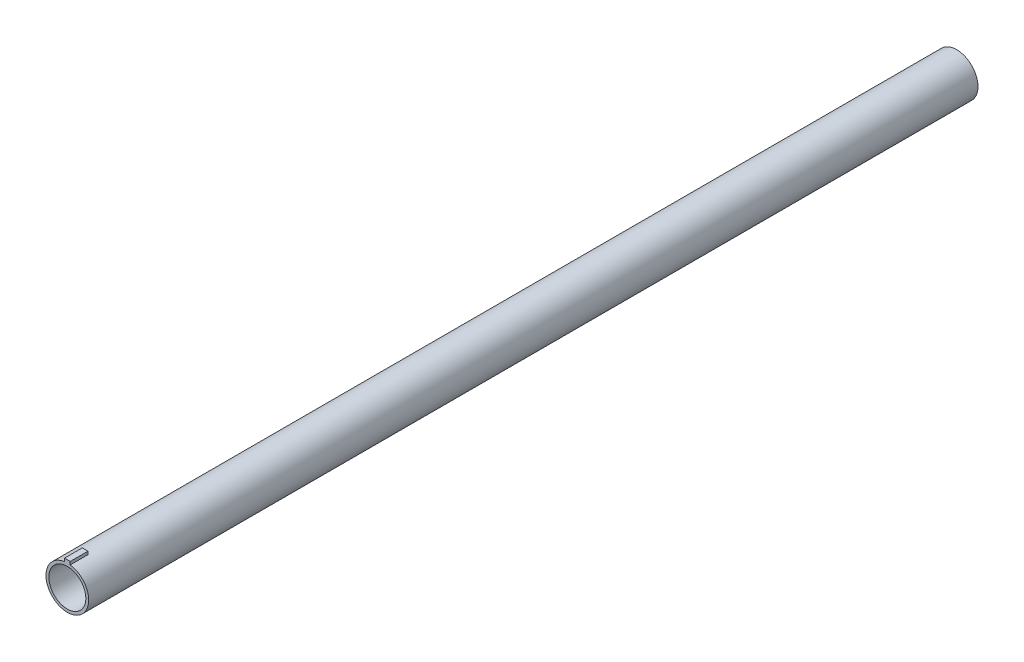
SolidWorks part; units mm, degrees
ref_plane "Front Plane" through (0, 0, 0) normal (0, 0, 1) x (1, 0, 0)
ref_plane "Top Plane" through (0, 0, 0) normal (0, 1, 0) x (1, 0, 0)
ref_plane "Right Plane" through (0, 0, 0) normal (1, 0, 0) x (0, 0, -1)
sketch "Sketch1" plane through (0, 0, 0) normal (0, 0, 1) x (1, 0, 0)
  circle A0 centre (0, 0) radius 30
  circle A1 centre (0, 0) radius 26
  dimension "D1" = 60
  dimension "D2" = 52
extrude "Boss-Extrude1" add sketch "Sketch1" along normal blind 1250
sketch "Sketch2" plane through (0, 0, 0) normal (0, 1, 0) x (1, 0, 0)
  line L0 (-30, -1250) -> (30, -1250) construction
  circle A0 centre (0, -1175) radius 15
  circle A1 centre (0, -1075) radius 15
  circle A2 centre (0, -975) radius 15
  circle A3 centre (0, -875) radius 15
  circle A4 centre (0, -775) radius 15
  circle A5 centre (0, -675) radius 15
  circle A6 centre (0, -575) radius 15
  circle A7 centre (0, -475) radius 15
  circle A8 centre (0, -375) radius 15
  circle A9 centre (0, -275) radius 15
  circle A10 centre (0, -175) radius 15
  circle A11 centre (0, -75) radius 15
  dimension "D1" = 30
  dimension "D2" = 75
  dimension "D3" = 12
extrude "Cut-Extrude1" cut sketch "Sketch2" against normal blind 30 contours A0 | A1 | A2 | A3 | A4 | A5 | A6 | A7 | A11 | A10 | A9 | A8
sketch "Sketch3" plane through (0, 0, 1250) normal (0, 0, 1) x (1, 0, 0)
  line L1 (0, 26) -> (-4, 26)
  line L2 (0, 26) -> (0, 34)
  line L3 (0, 34) -> (-4, 34)
  line L4 (-4, 26) -> (-4, 34)
  line L6 (0, 26) -> (4, 26)
  line L7 (0, 26) -> (0, 34)
  line L8 (0, 34) -> (4, 34)
  line L9 (4, 26) -> (4, 34)
  circle A0 centre (0, 0) radius 26 construction
  circle M5 centre (0, 0) radius 30
  dimension "D1" = 8
  dimension "D2" = 4
  dimension "D3" = 4
extrude "Boss-Extrude2" add sketch "Sketch3" against normal blind 25 contours L9 L8 L2 M5 | L4 L2 L3 M5 | L4 L1 L2 M5 | L6 L9 L2 M5
